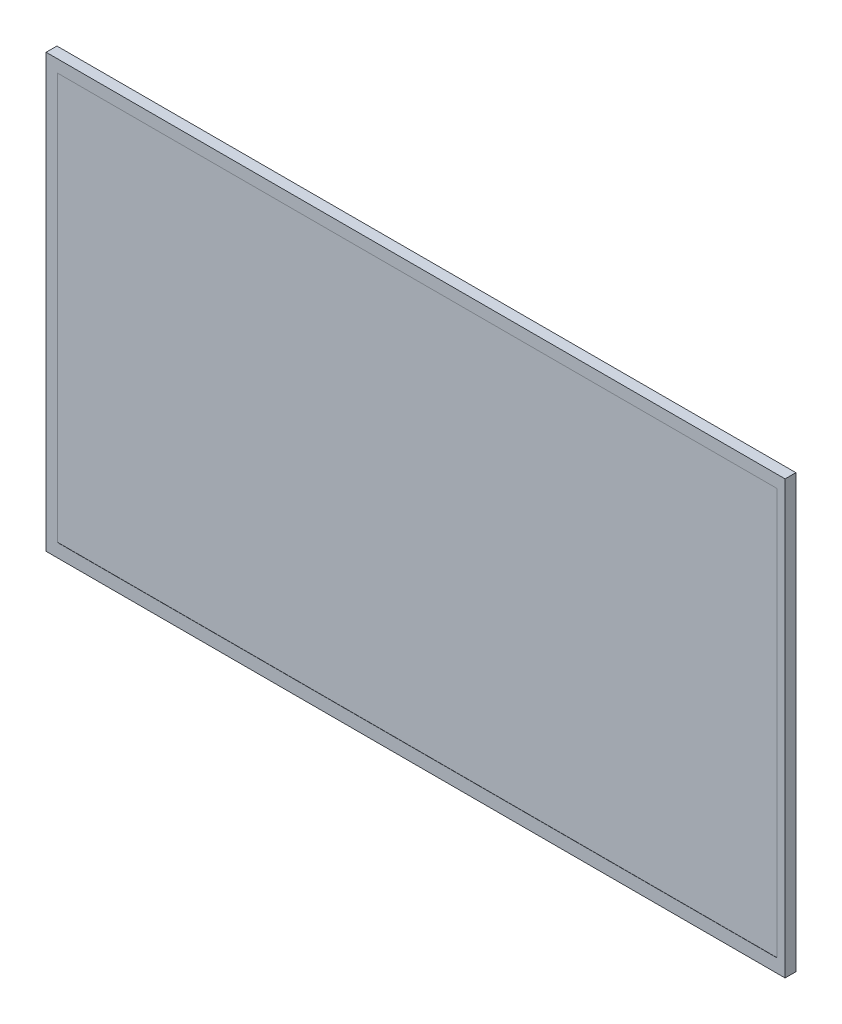
SolidWorks part; units mm, degrees
ref_plane "Front Plane" through (0, 0, 0) normal (0, 0, 1) x (1, 0, 0)
ref_plane "Top Plane" through (0, 0, 0) normal (0, 1, 0) x (1, 0, 0)
ref_plane "Right Plane" through (0, 0, 0) normal (1, 0, 0) x (0, 0, -1)
sketch "Sketch2" plane through (0, 0, 0) normal (0, 0, 1) x (1, 0, 0)
  line L0 (-179.5, 105) -> (179.5, -105) construction
  line L1 (-179.5, 105) -> (179.5, 105)
  line L2 (-179.5, 105) -> (-179.5, -105)
  line L3 (-179.5, -105) -> (179.5, -105)
  line L4 (179.5, 105) -> (179.5, -105)
  point P4 (0, 0)
  dimension "D1" = 359
  dimension "D2" = 210
extrude "Boss-Extrude1" add sketch "Sketch2" along normal blind 5.25
sketch "Sketch3" plane through (0, 0, 5.25) normal (0, 0, 1) x (1, 0, 0)
  line L0 (179.5, 105) -> (-179.5, 105) construction
  line L1 (-174, 99) -> (175.5, 99)
  line L2 (-174, 99) -> (-174, -98.5)
  line L3 (-174, -98.5) -> (175.5, -98.5)
  line L4 (175.5, 99) -> (175.5, -98.5)
  line L5 (-179.5, 105) -> (-179.5, -105) construction
  line L6 (179.5, -105) -> (179.5, 105) construction
  line L7 (-179.5, -105) -> (179.5, -105) construction
  dimension "D1" = 6
  dimension "D2" = 5.5
  dimension "D3" = 4
  dimension "D4" = 6.5
extrude "Cut-Extrude1" cut sketch "Sketch3" against normal blind 0.1
sketch "Sketch4" plane through (0, 0, 0) normal (0, 0, -1) x (-1, 0, 0)
  line L0 (-71.8, -69) -> (-71.8, -70)
  line L1 (-71.8, -67) -> (-50.8, -67)
  line L2 (-74.3, -68) -> (-48.3, -68) construction
  line L3 (-71.8, -69) -> (-50.8, -69)
  line L4 (-61.3, -69) -> (-61.3, -67) construction
  line L5 (-74.3, -66) -> (-71.8, -66)
  line L6 (-74.3, -66) -> (-74.3, -70)
  line L7 (-74.3, -70) -> (-71.8, -70)
  line L8 (-71.8, -66) -> (-71.8, -67)
  line L9 (-179.5, -105) -> (-179.5, 105) construction
  line L10 (-50.8, -66) -> (-50.8, -67)
  line L11 (-48.3, -70) -> (-50.8, -70)
  line L12 (-48.3, -66) -> (-48.3, -70)
  line L13 (-48.3, -66) -> (-50.8, -66)
  line L14 (-50.8, -69) -> (-50.8, -70)
  line L15 (179.5, -105) -> (-179.5, -105) construction
  point P11 (-61.3, -68)
  dimension "D1" = 2
  dimension "D2" = 105.2
  dimension "D3" = 4
  dimension "D4" = 2.5
  dimension "D5" = 36
  dimension "D6" = 10.5
extrude "Boss-Extrude2" add sketch "Sketch4" along normal blind 1
sketch "Sketch5" plane through (0, 0, 0) normal (0, 0, -1) x (-1, 0, 0)
  line L0 (179.5, -105) -> (-179.5, -105) construction
  line L1 (-113.5, -64) -> (113, -64)
  line L2 (-113.5, -64) -> (-113.5, -105)
  line L3 (-113.5, -105) -> (113, -105)
  line L4 (113, -64) -> (113, -105)
  line L5 (-179.5, -105) -> (-179.5, 105) construction
  line L6 (179.5, 105) -> (179.5, -105) construction
  dimension "D1" = 41
  dimension "D2" = 66
  dimension "D3" = 66.5
extrude "Boss-Extrude3" add sketch "Sketch5" along normal blind 0.25
